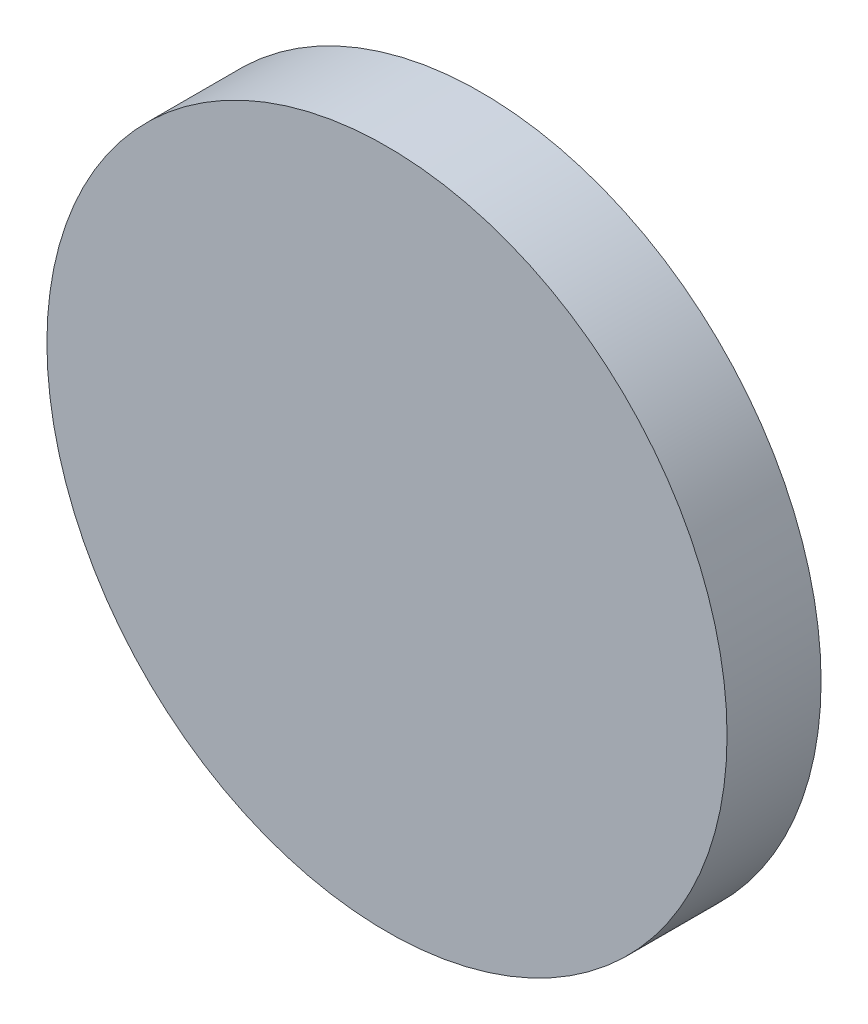
SolidWorks part; units mm, degrees
ref_plane "Front Plane" through (0, 0, 0) normal (0, 0, 1) x (1, 0, 0)
ref_plane "Top Plane" through (0, 0, 0) normal (0, 1, 0) x (1, 0, 0)
ref_plane "Right Plane" through (0, 0, 0) normal (1, 0, 0) x (0, 0, -1)
sketch "Sketch1" plane through (0, 0, 0) normal (0, 0, 1) x (1, 0, 0)
  circle A0 centre (0, 0) radius 10.85
  dimension "D1" = 21.7
extrude "Boss-Extrude1" add sketch "Sketch1" along normal blind 3 contours A0
